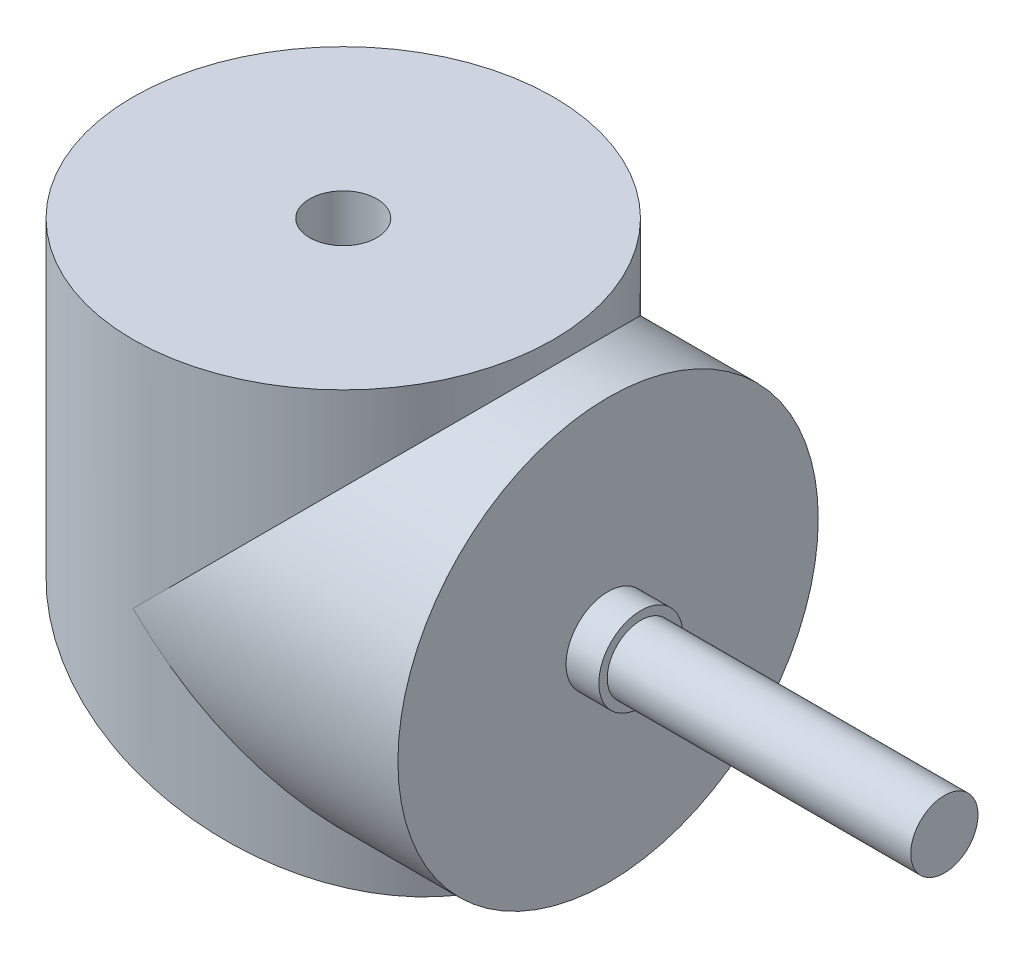
SolidWorks part; units mm, degrees
ref_plane "Front Plane" through (0, 0, 0) normal (0, 0, 1) x (1, 0, 0)
ref_plane "Top Plane" through (0, 0, 0) normal (0, 1, 0) x (1, 0, 0)
ref_plane "Right Plane" through (0, 0, 0) normal (1, 0, 0) x (0, 0, -1)
sketch "Sketch1" plane through (0, 0, 0) normal (1, 0, 0) x (0, 0, -1)
  circle A0 centre (0, 0) radius 37.5
  dimension "D1" = 75
extrude "Boss-Extrude1" add sketch "Sketch1" along normal blind 47.25
sketch "Sketch2" plane through (0, 0, 0) normal (0, 1, 0) x (1, 0, 0)
  circle A0 centre (0, 0) radius 37.5
  dimension "D1" = 75
extrude "Boss-Extrude2" add sketch "Sketch2" along normal blind 41.55 and the other way blind 39.7046
sketch "Sketch3" plane through (0, 0, 0) normal (0, 0, 1) x (1, 0, 0)
  line L0 (37.5, -39.7046) -> (-37.5, -39.7046)
  line L1 (-37.5, -39.7046) -> (-37.5, -9.7046)
  line L2 (-37.5, 41.55) -> (-37.5, -39.7046) construction
  line L3 (-37.5, -9.7046) -> (37.5, -39.7046)
  dimension "D1" = 21.801
extrude "Cut-Extrude1" cut sketch "Sketch3" against normal through all both and the other way through all
sketch "Sketch4" plane through (47.25, 0, 0) normal (1, 0, 0) x (0, 0, -1)
  circle A0 centre (0, 0) radius 6
  dimension "D1" = 12
extrude "Boss-Extrude3" add sketch "Sketch4" along normal blind 60
sketch "Sketch5" plane through (47.25, 0, 0) normal (1, 0, 0) x (0, 0, -1)
  circle A0 centre (0, 0) radius 7.5
  dimension "D1" = 15
extrude "Boss-Extrude4" add sketch "Sketch5" along normal blind 5.85
sketch "Sketch6" plane through (0, 41.55, 0) normal (0, 1, 0) x (1, 0, 0)
  circle A0 centre (0, 0) radius 6
  dimension "D1" = 12
extrude "Cut-Extrude2" cut sketch "Sketch6" against normal blind 58.15
